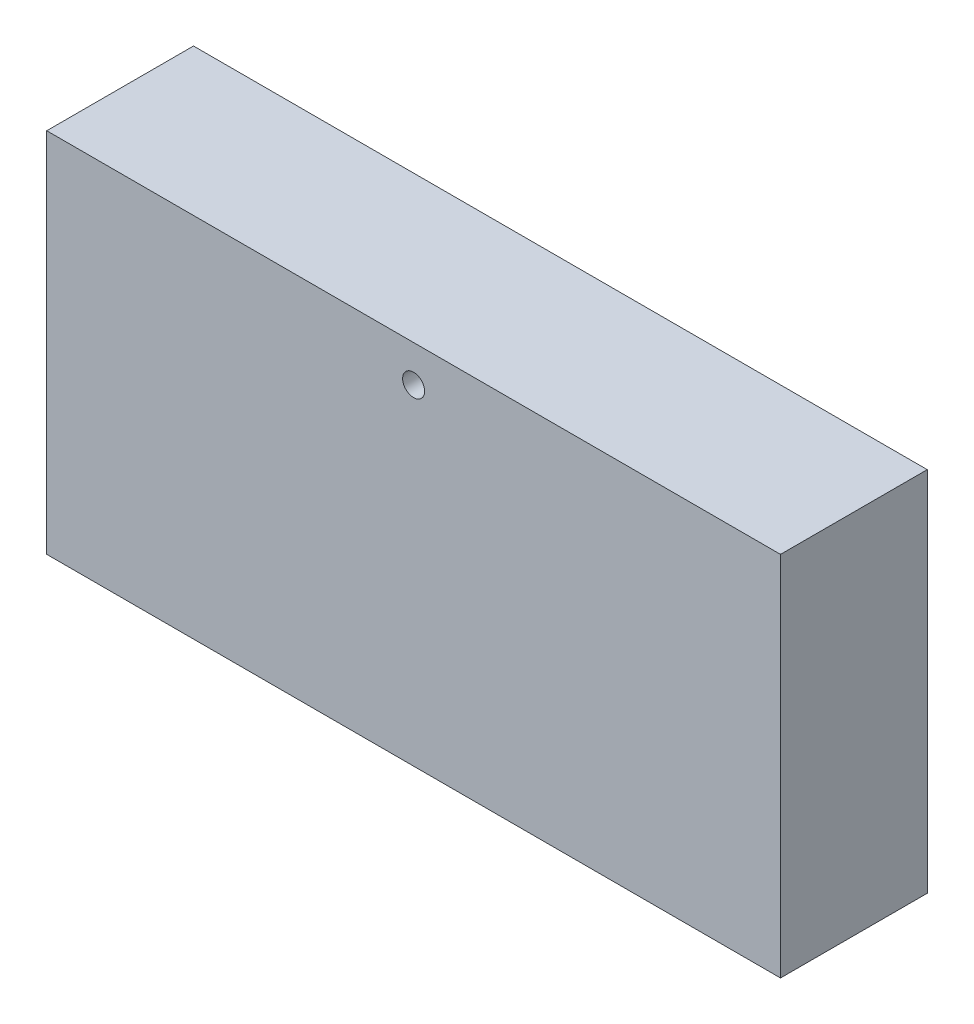
SolidWorks part; units mm, degrees
ref_plane "Front Plane" through (0, 0, 0) normal (0, 0, 1) x (1, 0, 0)
ref_plane "Top Plane" through (0, 0, 0) normal (0, 1, 0) x (1, 0, 0)
ref_plane "Right Plane" through (0, 0, 0) normal (1, 0, 0) x (0, 0, -1)
sketch "Sketch1" plane through (0, 0, 0) normal (0, 0, 1) x (1, 0, 0)
  line L0 (0, 17.9939) -> (0, -14.3929) construction
  line L1 (-50, 25) -> (50, 25)
  line L2 (-50, 25) -> (-50, -25)
  line L3 (-50, -25) -> (50, -25)
  line L4 (50, 25) -> (50, -25)
  line L5 (-50, 25) -> (50, -25) construction
  line L6 (-50, -25) -> (50, 25) construction
  circle A0 centre (0, 20) radius 1.5
  point P0 (0, 0)
  dimension "D1" = 3
  dimension "D2" = 100
  dimension "D3" = 50
  dimension "D4" = 20
extrude "Boss-Extrude1" add sketch "Sketch1" along normal blind 20
